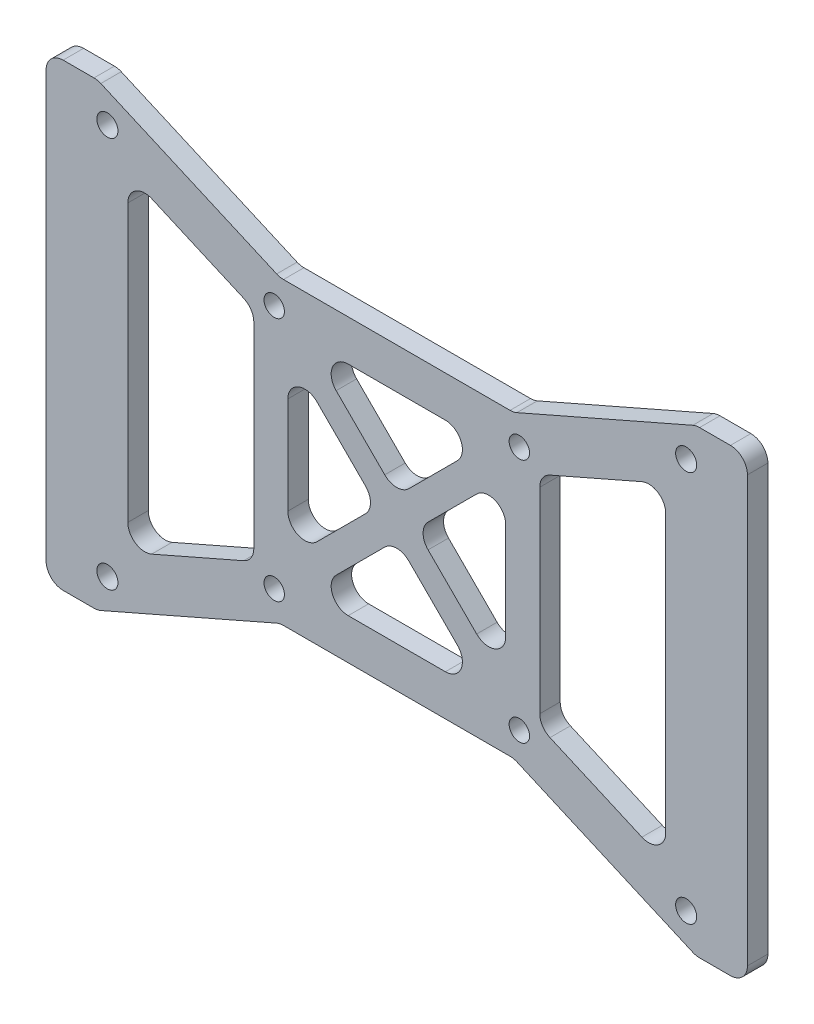
SolidWorks part; units mm, degrees
material "Thornel Mat VMA"
ref_plane "前视基准面" through (0, 0, 0) normal (0, 0, 1) x (1, 0, 0)
ref_plane "上视基准面" through (0, 0, 0) normal (0, 1, 0) x (1, 0, 0)
ref_plane "右视基准面" through (0, 0, 0) normal (1, 0, 0) x (0, 0, -1)
sketch "草图1" plane through (0, 0, 0) normal (0, 0, 1) x (1, 0, 0)
  line L1 (51.5, -33.725) -> (-51.5, -33.725)
  line L2 (51.5, -33.725) -> (51.5, 33.725)
  line L3 (51.5, 33.725) -> (-51.5, 33.725)
  line L4 (-51.5, -33.725) -> (-51.5, 33.725)
  line L5 (51.5, -33.725) -> (-51.5, 33.725) construction
  line L6 (51.5, 33.725) -> (-51.5, -33.725) construction
  point P0 (0, 0)
  dimension "D1" = 67.45
  dimension "D2" = 103
extrude "凸台-拉伸1" add sketch "草图1" along normal blind 3
sketch "草图2" plane through (0, 0, 3) normal (0, 0, 1) x (1, 0, 0)
  line L0 (0, 0) -> (-50000, 0) construction
  line L1 (0, 0) -> (0, 50000) construction
  circle A0 centre (-18, 18) radius 1.5
  circle A1 centre (18, 18) radius 1.5
  circle A2 centre (18, -18) radius 1.5
  circle A3 centre (-18, -18) radius 1.5
  circle A4 centre (-42.5, 28.725) radius 1.55
  circle A5 centre (-42.5, -28.725) radius 1.55
  circle A6 centre (42.5, -28.725) radius 1.55
  circle A7 centre (42.5, 28.725) radius 1.55
  dimension "D1" = 3
  dimension "D4" = 3.1
  dimension "D2" = 36
  dimension "D3" = 36
extrude "切除-拉伸1" cut sketch "草图2" against normal blind 10
sketch "草图3" plane through (0, 0, 3) normal (0, 0, 1) x (1, 0, 0)
  line L0 (-42.5, 28.725) -> (-42.5, -28.725) construction
  line L1 (-42.5, -28.725) -> (-18, -18) construction
  line L2 (-18, -18) -> (-18, 18) construction
  line L3 (-18, 18) -> (-42.5, 28.725) construction
  line L4 (-42.5, 28.725) -> (42.5, 28.725) construction
  line L5 (42.5, 28.725) -> (18, 18) construction
  line L6 (18, 18) -> (-18, 18) construction
  line L7 (18, -18) -> (18, 18) construction
  line L8 (42.5, 28.725) -> (42.5, -28.725) construction
  line L9 (42.5, -28.725) -> (18, -18) construction
  line L10 (-18, -18) -> (18, -18) construction
  line L11 (-42.5, -28.725) -> (42.5, -28.725) construction
  line L12 (-39.5, 24.1369) -> (-39.5, -24.1369)
  line L13 (-39.5, -24.1369) -> (-21, -16.0384)
  line L14 (-21, -16.0384) -> (-21, 16.0384)
  line L15 (-21, 16.0384) -> (-39.5, 24.1369)
  line L16 (-17.1628, 22) -> (-23.3878, 24.725)
  line L17 (-23.3878, 24.725) -> (23.3878, 24.725) construction
  line L18 (23.3878, 24.725) -> (17.1628, 22)
  line L19 (17.1628, 22) -> (-17.1628, 22)
  line L20 (39.5, 24.1369) -> (21, 16.0384)
  line L21 (21, -16.0384) -> (21, 16.0384)
  line L22 (39.5, -24.1369) -> (21, -16.0384)
  line L23 (39.5, 24.1369) -> (39.5, -24.1369)
  line L24 (-23.3878, -24.725) -> (-17.1628, -22)
  line L25 (-17.1628, -22) -> (17.1628, -22)
  line L26 (23.3878, -24.725) -> (17.1628, -22)
  line L27 (-23.3878, -24.725) -> (23.3878, -24.725) construction
  line L28 (0, 0) -> (-18, 18) construction
  line L29 (-18, -18) -> (0, 0) construction
  line L30 (0, 0) -> (18, 18) construction
  line L31 (0, 0) -> (18, -18) construction
  line L32 (-2.8284, 0) -> (-16, 13.1716)
  line L33 (-16, -13.1716) -> (-16, 13.1716)
  line L34 (-16, -13.1716) -> (-2.8284, 0)
  line L35 (13.1716, 16) -> (-13.1716, 16)
  line L36 (0, 2.8284) -> (-13.1716, 16)
  line L37 (0, 2.8284) -> (13.1716, 16)
  line L38 (2.8284, 0) -> (16, 13.1716)
  line L39 (16, -13.1716) -> (16, 13.1716)
  line L40 (2.8284, 0) -> (16, -13.1716)
  line L41 (-13.1716, -16) -> (0, -2.8284)
  line L42 (0, -2.8284) -> (13.1716, -16)
  line L43 (-13.1716, -16) -> (13.1716, -16)
  line L44 (-23.3878, -24.725) -> (-43.9472, -33.725)
  line L45 (-51.5, -33.725) -> (51.5, -33.725) construction
  line L46 (-43.9472, -33.725) -> (43.9472, -33.725)
  line L47 (43.9472, -33.725) -> (23.3878, -24.725)
  line L48 (0, 0) -> (-50000, 0) construction
  line L49 (0, 0) -> (0, 50000) construction
  line L50 (-23.3878, 24.725) -> (-43.9472, 33.725)
  line L51 (51.5, 33.725) -> (-51.5, 33.725) construction
  line L52 (23.3878, 24.725) -> (43.9472, 33.725)
  line L53 (43.9472, 33.725) -> (-43.9472, 33.725)
  dimension "D1" = 3
  dimension "D2" = 4
  dimension "D3" = 3
  dimension "D4" = 4
  dimension "D5" = 2
  dimension "D6" = 2
  dimension "D7" = 2
  dimension "D8" = 2
extrude "切除-拉伸2" cut sketch "草图3" against normal blind 10
fillet "圆角2" radius 2.5 32 edges at (17.1628, -22, 1.5) (43.9472, -33.725, 1.5) (51.5, -33.725, 1.5) (51.5, 33.725, 1.5) (43.9472, 33.725, 1.5) (17.1628, 22, 1.5) (-17.1628, 22, 1.5) (-43.9472, 33.725, 1.5) (-51.5, 33.725, 1.5) (-51.5, -33.725, 1.5) (-17.1628, -22, 1.5) (-43.9472, -33.725, 1.5) (-21, -16.0384, 1.5) (-39.5, -24.1369, 1.5) (-21, 16.0384, 1.5) (16, 13.1716, 1.5) (16, -13.1716, 1.5) (2.8284, 0, 1.5) (-13.1716, 16, 1.5) (13.1716, 16, 1.5) (0, 2.8284, 1.5) (0, -2.8284, 1.5) (13.1716, -16, 1.5) (-13.1716, -16, 1.5) (21, -16.0384, 1.5) (21, 16.0384, 1.5) (39.5, 24.1369, 1.5) (39.5, -24.1369, 1.5) (-16, 13.1716, 1.5) (-2.8284, 0, 1.5) (-16, -13.1716, 1.5) (-39.5, 24.1369, 1.5)
